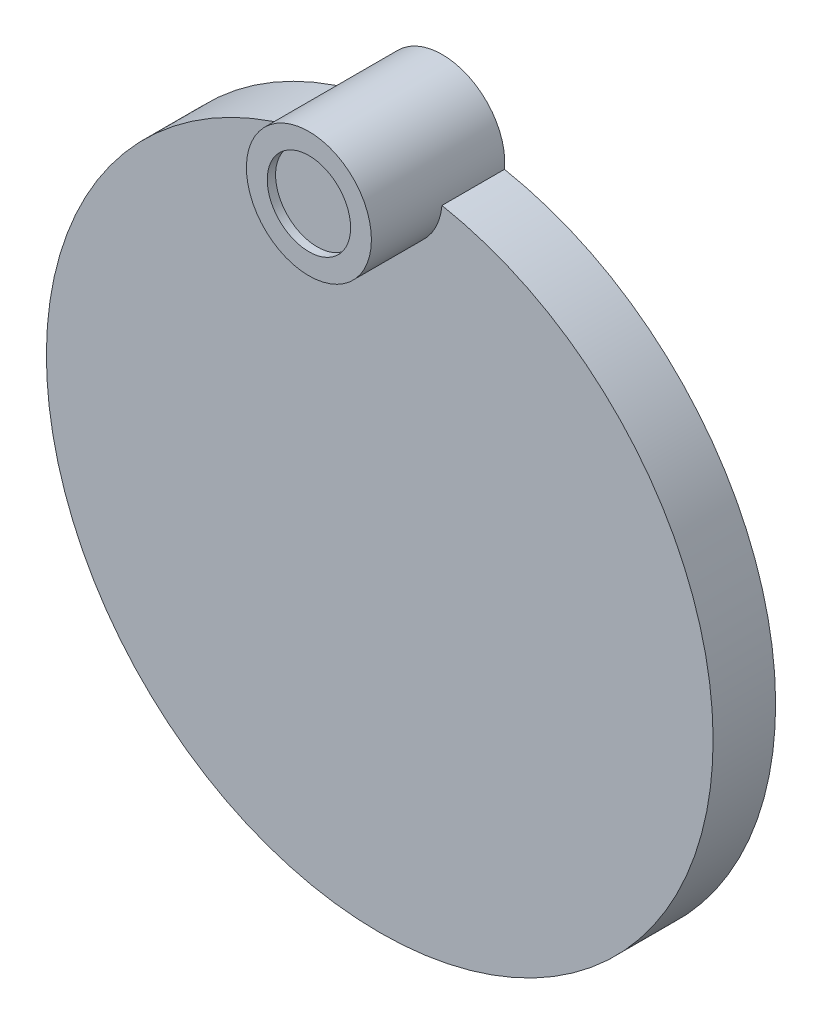
SolidWorks part; units mm, degrees
ref_plane "正面" through (0, 0, 0) normal (0, 0, 1) x (1, 0, 0)
ref_plane "平面" through (0, 0, 0) normal (0, 1, 0) x (1, 0, 0)
ref_plane "右側面" through (0, 0, 0) normal (1, 0, 0) x (0, 0, -1)
sketch "ｽｹｯﾁ4" plane through (0, 0, 0) normal (0, 0, 1) x (1, 0, 0)
  arc A1 (-14.9339, -1.4063) -> (9.9804, -0.625) centre (0, -80) ccw
  arc A3 (14.9339, -1.4063) -> (-14.9339, -1.4063) centre (0, 0) ccw
  dimension "D4" = 30
  dimension "D2" = 80
extrude "ﾎﾞｽ - 押し出し1" add sketch "ｽｹｯﾁ4" along normal blind 15
sketch "ｽｹｯﾁ5" plane through (0, 0, 15) normal (0, 0, 1) x (1, 0, 0)
  circle A0 centre (0, 0) radius 15
  dimension "D1" = 30
extrude "ﾎﾞｽ - 押し出し3" add sketch "ｽｹｯﾁ5" along normal blind 17
sketch "ｽｹｯﾁ9" plane through (0, 0, 32) normal (0, 0, 1) x (1, 0, 0)
  circle A0 centre (0, 0) radius 10
  dimension "D1" = 20
extrude "ｶｯﾄ - 押し出し2" cut sketch "ｽｹｯﾁ9" against normal blind 2
